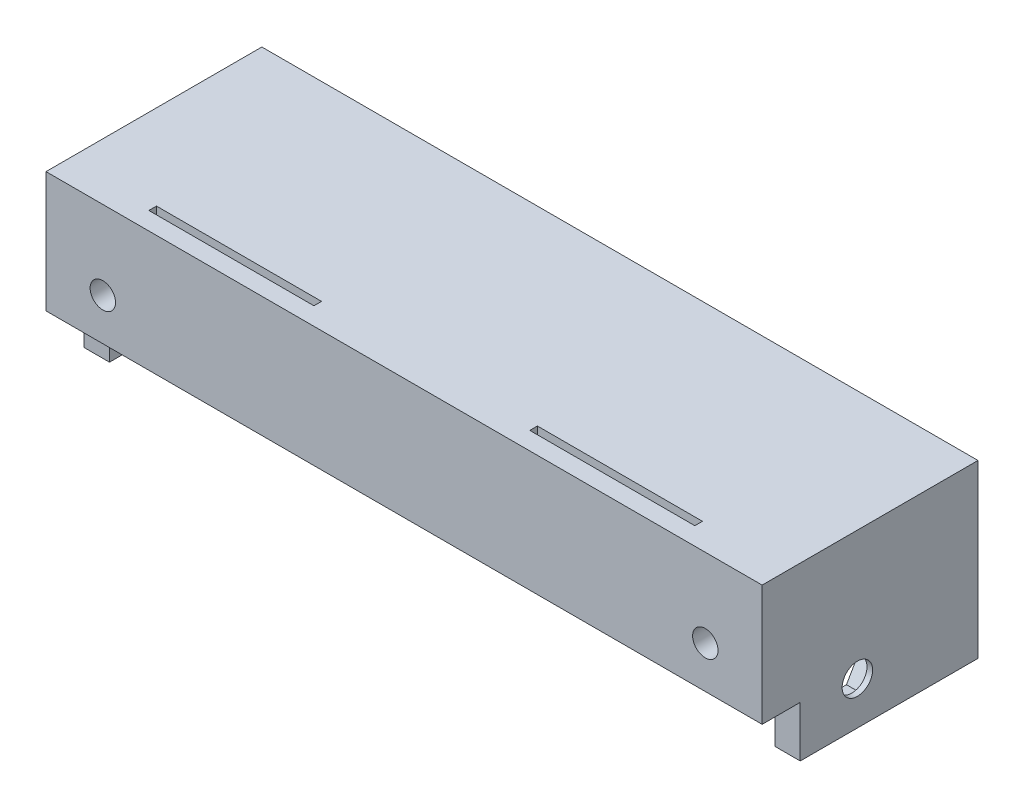
SolidWorks part; units mm, degrees
ref_plane "Piano frontale" through (0, 0, 0) normal (0, 0, 1) x (1, 0, 0)
ref_plane "Piano superiore" through (0, 0, 0) normal (0, 1, 0) x (1, 0, 0)
ref_plane "Piano destro" through (0, 0, 0) normal (1, 0, 0) x (0, 0, -1)
sketch "Schizzo1" plane through (0, 0, 0) normal (0, 0, 1) x (1, 0, 0)
  line L0 (-28.2, 0) -> (28.2, 0)
  line L1 (0, 0) -> (0, -48.4131) construction
  line L2 (-28.2, 0) -> (-28.2, -9.5)
  line L3 (-28.2, -9.5) -> (28.2, -9.5)
  line L4 (28.2, 0) -> (28.2, -9.5)
  circle A0 centre (-23.725, -6.2) radius 1
  circle A1 centre (23.725, -6.2) radius 1
  point P7 (0, -9.5)
  dimension "D4" = 2
  dimension "D1" = 56.4
  dimension "D2" = 9.5
  dimension "D3" = 3.3
  dimension "D5" = 47.45
extrude "Estrusione-Estrusione1" add sketch "Schizzo1" along normal blind 3
sketch "Schizzo2" plane through (0, 0, 0) normal (0, 0, -1) x (-1, 0, 0)
  line L0 (28.2, 0) -> (28.2, -9.5) construction
  line L1 (-28.2, 0) -> (28.2, 0)
  line L2 (-28.2, 0) -> (-28.2, -3)
  line L3 (-28.2, -3) -> (28.2, -3)
  line L4 (28.2, 0) -> (28.2, -3)
  dimension "D1" = 3
extrude "Estrusione-Estrusione2" add sketch "Schizzo2" along normal blind 14
sketch "Schizzo3" plane through (28.2, 0, 0) normal (1, 0, 0) x (0, 0, -1)
  line L0 (14, 0) -> (14, -3) construction
  line L1 (0, -3) -> (14, -3)
  line L2 (0, -3) -> (0, -13.5)
  line L3 (0, -13.5) -> (14, -13.5)
  line L4 (14, -3) -> (14, -13.5)
  line L6 (0, -9.5) -> (0, -3) construction
  line L7 (14, -3) -> (0, -3) construction
  dimension "D1" = 10.5
extrude "Estrusione-Estrusione3" add sketch "Schizzo3" against normal blind 2
hole_wizard "Foro per Vite M2-1" positions "Schizzo5" profile "Schizzo4" hole size "M2" standard "Ansi Metric" end condition up to next
sketch "Schizzo5" plane through (28.2, 0, 0) normal (1, 0, 0) x (0, 0, -1)
  line L1 (0, -3) -> (0, -9.5) construction
  line L2 (0, -3.94) -> (9, -3.94) construction
  point P0 (4.5, -10.14)
  dimension "D1" = 4.5
  dimension "D2" = 6.2
sketch "Schizzo4" plane through (28.2, -10.14, -4.5) normal (0, 1, 0) x (0, 0, -1)
  line L0 (0, 0) -> (0, 56.4)
  line L1 (0, 56.4) -> (1.2, 56.4)
  line L2 (1.2, 56.4) -> (1.2, 0)
  line L5 (1.2, 0) -> (0, 0)
  line L11 (0, -6.35) -> (0, 107.95) construction
  dimension "Thru Hole Dia." = 2.4
  dimension "Thru Hole Depth" = 56.4
sketch "Schizzo6" plane through (26.2, 0, 0) normal (-1, 0, 0) x (0, 0, 1)
  line L1 (-5.6403, -8.165) -> (-6.7805, -10.14)
  line L2 (-6.7805, -10.14) -> (-5.6403, -12.115)
  line L3 (-5.6403, -12.115) -> (-3.3597, -12.115)
  line L4 (-3.3597, -12.115) -> (-2.2195, -10.14)
  line L5 (-2.2195, -10.14) -> (-3.3597, -8.165)
  line L6 (-3.3597, -8.165) -> (-5.6403, -8.165)
  circle A0 centre (-4.5, -10.14) radius 1.975 construction
  dimension "D1" = 3.95
extrude "Taglio-Estrusione1" cut sketch "Schizzo6" against normal blind 1.56
mirror "Specchia2" about plane through (0, 0, 0) normal (1, 0, 0) of "Taglio-Estrusione1", "Foro per Vite M2-1", "Estrusione-Estrusione3"
extrude "Taglio-Estrusione3" cut sketch "Schizzo8" along normal through all from surface contours L2 L5 L4 L3
sketch "Schizzo8" plane through (0, 0, -9) normal (0, 1, 0) x (1, 0, 0)
  line L0 (0, -9) -> (0, -12) construction
  line L1 (8.5, -10) -> (8.5, -10.6)
  line L2 (-8.5, -10) -> (-21.5, -10)
  line L3 (-8.5, -10) -> (-8.5, -10.6)
  line L4 (-8.5, -10.6) -> (-21.5, -10.6)
  line L5 (-21.5, -10) -> (-21.5, -10.6)
  line L6 (8.5, -10.6) -> (21.5, -10.6)
  line L7 (21.5, -10) -> (21.5, -10.6)
  line L16 (-28.2, -9) -> (-28.2, -12) construction
  line L19 (26.2, -9) -> (-26.2, -9) construction
  line L22 (28.2, -12) -> (28.2, -9) construction
  line L23 (-28.2, -12) -> (28.2, -12) construction
  line L24 (8.5, -10) -> (21.5, -10)
  line L26 (-20, -10) -> (-10, -10)
  line L28 (-15, -10) -> (-15, -10.6) construction
  line L361 (-26.2, -9) -> (-28.2, -9)
  line L363 (28.2, -9) -> (26.2, -9)
